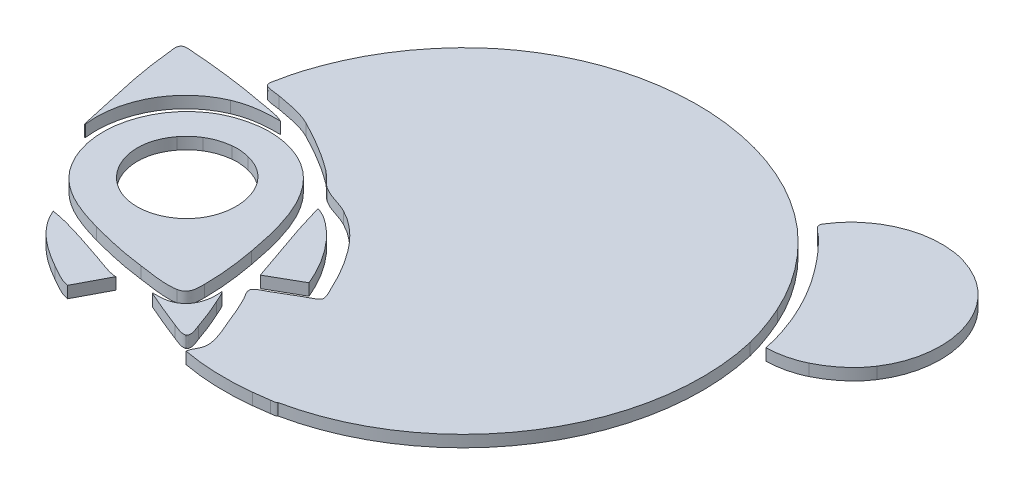
SolidWorks part; units mm, degrees
ref_plane "Alzado" through (0, 0, 0) normal (0, 0, 1) x (1, 0, 0)
ref_plane "Planta" through (0, 0, 0) normal (0, 1, 0) x (1, 0, 0)
ref_plane "Vista lateral" through (0, 0, 0) normal (1, 0, 0) x (0, 0, -1)
sketch "Croquis2" plane through (0, 0, 0) normal (0, 1, 0) x (1, 0, 0)
  line L1 (-10.1434, 10.8277) -> (39.8566, 10.8277)
  line L2 (-10.1434, 10.8277) -> (-10.1434, -4.1723)
  line L3 (-10.1434, -4.1723) -> (39.8566, -4.1723)
  line L4 (39.8566, 10.8277) -> (39.8566, -4.1723)
  line L5 (-10.1434, 10.8277) -> (39.8566, -4.1723) construction
  line L6 (-10.1434, -4.1723) -> (39.8566, 10.8277) construction
  point P0 (14.8566, 3.3277)
  dimension "D1" = 50
  dimension "D2" = 15
sketch "Croquis1" plane through (0, 0, 0) normal (0, 1, 0) x (1, 0, 0)
  line L0 (3.5784, 3.9291) -> (1.8314, 3.9291)
  line L1 (3.9335, 5.4773) -> (5.155, 5.4773)
  line L2 (5.155, 5.4773) -> (5.155, 2.4804)
  line L3 (5.155, 2.4804) -> (5.1692, 2.4804)
  line L4 (3.0387, 4.4262) -> (4.0755, 4.4262)
  line L5 (4.0755, 4.4262) -> (4.0755, -0.829)
  line L6 (4.0755, -0.829) -> (4.0755, -2.0789)
  line L7 (4.2602, -2.5051) -> (4.6579, -2.5051)
  line L8 (4.6579, -2.5051) -> (4.6579, 4.9802)
  line L9 (4.6579, 4.9802) -> (3.9193, 4.9802)
  line L10 (3.9193, 4.9802) -> (3.5926, 4.9716)
  line L11 (3.5926, 4.9716) -> (3.408, 4.8097)
  line L12 (3.408, 4.8097) -> (3.0387, 4.4262)
  line L13 (18.6341, 4.8097) -> (18.6341, 0.7333)
  line L14 (20.0828, -2.3346) -> (20.0828, -1.9369)
  line L15 (19.2164, -0.7154) -> (19.2164, 2.8781)
  line L16 (19.2164, 2.8781) -> (20.0828, 2.8781)
  line L17 (20.0828, 2.8781) -> (20.0828, 3.2758)
  line L18 (20.0828, 3.2758) -> (20.0682, 3.4234)
  line L19 (20.0682, 3.4234) -> (19.8556, 3.4462)
  line L20 (19.8556, 3.4462) -> (19.2164, 3.4462)
  line L21 (19.2164, 3.4462) -> (19.2164, 4.8097)
  line L22 (19.2164, 4.8097) -> (18.6341, 4.8097)
  line L23 (23.8893, 4.8097) -> (23.8893, 0.8044)
  line L24 (25.3239, -2.505) -> (25.3239, -1.9369)
  line L25 (24.4717, -0.7296) -> (24.4717, 2.8781)
  line L26 (24.4717, 2.8781) -> (25.3239, 2.8781)
  line L27 (25.3239, 2.8781) -> (25.3239, 3.4462)
  line L28 (25.3239, 3.4462) -> (24.4717, 3.4462)
  line L29 (24.4717, 3.4462) -> (24.4717, 4.8097)
  line L30 (24.4717, 4.8097) -> (23.8893, 4.8097)
  line L31 (-5.0999, 1.3015) -> (-5.0857, 1.3015)
  line L32 (5.5953, -2.505) -> (6.1634, -2.505)
  line L33 (7.74, -2.505) -> (8.3082, -2.505)
  line L34 (8.3082, -2.505) -> (8.3082, 1.5856)
  line L35 (5.5953, 0.6765) -> (5.5953, -2.505)
  line L36 (12.8249, 0.0267) -> (13.9469, 0.5878)
  line L37 (11.7312, 1.4009) -> (11.7312, -0.3177)
  line L38 (14.2736, -0.7296) -> (13.8759, -0.7296)
  line L39 (17.2989, -2.505) -> (17.725, -2.505)
  line L40 (17.8813, -2.0789) -> (17.8813, -1.0989)
  line L41 (15.1542, 1.2731) -> (15.1542, -0.7864)
  line L42 (15.1542, -0.7864) -> (15.1542, -2.0647)
  line L43 (15.7365, -2.2494) -> (15.7365, -1.525)
  line L44 (15.7365, -1.525) -> (15.7365, 1.1026)
  line L45 (17.2989, 1.1737) -> (17.2989, -0.3035)
  line L46 (17.2989, -0.3035) -> (17.2989, -2.505)
  line L47 (20.4521, 1.2447) -> (20.4521, -0.3319)
  line L48 (28.4202, -0.7296) -> (27.8521, -0.7296)
  line L49 (26.7868, 0.0197) -> (27.8379, 0.5452)
  line L50 (28.4202, 0.989) -> (28.4202, 1.4577)
  line L51 (25.7074, 1.3015) -> (25.7074, -0.6444)
  line L52 (31.687, -0.7864) -> (31.1189, -0.7864)
  line L53 (29.6559, -0.687) -> (29.6559, 1.3583)
  line L54 (31.1189, 1.7276) -> (31.687, 1.7276)
  line L55 (29.0878, 1.6992) -> (29.0878, -0.5876)
  line L56 (34.4851, -2.2352) -> (34.4851, -2.505)
  line L57 (34.4851, -2.505) -> (35.0248, -2.505)
  line L58 (35.0248, -2.505) -> (35.0248, 0.0658)
  line L59 (35.0248, 0.0658) -> (35.0248, 1.8696)
  line L60 (32.312, 1.5288) -> (32.312, -0.4029)
  line L61 (8.6632, 3.4462) -> (8.7709, 2.8213)
  line L62 (8.7709, 2.8213) -> (9.0496, 1.3583)
  line L63 (9.0496, 1.3583) -> (9.7853, -2.505)
  line L64 (10.5409, -1.1415) -> (11.1318, 1.9122)
  line L65 (11.4187, 3.4462) -> (10.8506, 3.4462)
  line L66 (10.041, -0.9853) -> (10.0268, -0.9853)
  line L67 (10.0268, -0.9853) -> (9.2456, 3.4462)
  line L68 (9.2456, 3.4462) -> (8.6632, 3.4462)
  line L69 (-0.2279, 2.4094) -> (-0.0054, 1.685)
  line L70 (-0.0054, 1.685) -> (0.5106, 0.1936)
  line L71 (0.5106, 0.1936) -> (1.306, 0.6481)
  line L72 (-0.4694, -1.5818) -> (-0.4694, -1.596)
  line L73 (-1.7335, -2.5051) -> (-1.3074, -1.6955)
  spline S0 degree 3 poles (8.6064, 5.0654) (8.9077, 5.0656) (9.231, 5.1421) (9.5012, 5.275) knots 0 0 0 0 1 1 1 1
  spline S1 degree 3 poles (9.5012, 5.275) (9.8765, 5.4595) (10.2057, 5.7212) (10.4375, 6.0738) knots 0 0 0 0 1 1 1 1
  spline S2 degree 3 poles (10.4375, 6.0738) (11.1456, 7.1512) (10.8182, 8.6685) (9.6859, 9.3162) knots 0 0 0 0 1 1 1 1
  spline S3 degree 3 poles (9.6859, 9.3162) (9.4504, 9.4509) (9.1882, 9.5508) (8.9189, 9.5924) knots 0 0 0 0 1 1 1 1
  spline S4 degree 3 poles (8.9189, 9.5924) (8.2132, 9.7014) (7.5188, 9.4932) (6.9872, 9.0163) knots 0 0 0 0 1 1 1 1
  spline S5 degree 3 poles (6.9872, 9.0163) (6.8569, 8.8994) (6.7378, 8.7633) (6.642, 8.6163) knots 0 0 0 0 1 1 1 1
  spline S6 degree 3 poles (6.642, 8.6163) (6.6153, 8.5752) (6.5511, 8.5009) (6.5671, 8.4482) knots 0 0 0 0 1 1 1 1
  spline S7 degree 3 poles (6.5671, 8.4482) (6.5982, 8.3461) (6.7844, 8.2366) (6.8594, 8.1618) knots 0 0 0 0 1 1 1 1
  spline S8 degree 3 poles (6.8594, 8.1618) (7.0821, 7.9394) (7.2857, 7.7003) (7.4783, 7.4516) knots 0 0 0 0 1 1 1 1
  spline S9 degree 3 poles (7.4783, 7.4516) (8.0092, 6.7663) (8.4305, 5.9176) (8.6064, 5.0654) knots 0 0 0 0 1 1 1 1
  spline S10 degree 3 poles (1.249, -2.4482) (1.8259, -2.5553) (2.4283, -2.5697) (3.0103, -2.5074) knots 0 0 0 0 1 1 1 1
  spline S11 degree 3 poles (3.0103, -2.5074) (3.1485, -2.4926) (3.2849, -2.4771) (3.4222, -2.4541) knots 0 0 0 0 1 1 1 1
  spline S12 degree 3 poles (3.4222, -2.4541) (3.4634, -2.4472) (3.536, -2.4479) (3.5638, -2.4115) knots 0 0 0 0 1 1 1 1
  spline S13 degree 3 poles (3.5638, -2.4115) (3.6258, -2.3302) (3.5784, -2.0665) (3.5784, -1.9653) knots 0 0 0 0 1 1 1 1
  spline S14 degree 3 poles (3.5784, -1.9653) (3.5784, -1.5582) (3.5826, -1.1506) (3.5785, -0.7438) knots 0 0 0 0 1 1 1 1
  spline S15 degree 3 poles (3.5785, -0.7438) (3.5624, 0.8135) (3.5784, 2.3718) (3.5784, 3.9291) knots 0 0 0 0 1 1 1 1
  spline S16 degree 3 poles (1.8314, 3.9291) (2.196, 4.2937) (2.5619, 4.657) (2.9251, 5.0228) knots 0 0 0 0 1 1 1 1
  spline S17 degree 3 poles (2.9251, 5.0228) (3.0505, 5.1491) (3.2259, 5.4068) (3.3938, 5.4687) knots 0 0 0 0 1 1 1 1
  spline S18 degree 3 poles (3.3938, 5.4687) (3.5397, 5.5225) (3.7781, 5.4773) (3.9335, 5.4773) knots 0 0 0 0 1 1 1 1
  spline S19 degree 3 poles (5.1692, 2.4804) (5.1849, 2.6775) (5.2637, 2.8864) (5.3504, 3.0627) knots 0 0 0 0 1 1 1 1
  spline S20 degree 3 poles (5.3504, 3.0627) (5.4291, 3.2228) (5.5273, 3.3749) (5.6523, 3.503) knots 0 0 0 0 1 1 1 1
  spline S21 degree 3 poles (5.6523, 3.503) (6.1635, 4.0269) (6.9766, 4.092) (7.669, 4.0261) knots 0 0 0 0 1 1 1 1
  spline S22 degree 3 poles (7.669, 4.0261) (7.9276, 4.0015) (8.1757, 3.9433) (8.436, 3.9433) knots 0 0 0 0 1 1 1 1
  spline S23 degree 3 poles (8.436, 3.9433) (8.4211, 4.6648) (8.1948, 5.4069) (7.9006, 6.0596) knots 0 0 0 0 1 1 1 1
  spline S24 degree 3 poles (7.9006, 6.0596) (7.6039, 6.7178) (7.1847, 7.3109) (6.6748, 7.8209) knots 0 0 0 0 1 1 1 1
  spline S25 degree 3 poles (6.6748, 7.8209) (4.3405, 10.1551) (0.3296, 10.1882) (-1.9888, 7.7924) knots 0 0 0 0 1 1 1 1
  spline S26 degree 3 poles (-1.9888, 7.7924) (-2.5824, 7.179) (-3.048, 6.4468) (-3.3469, 5.6477) knots 0 0 0 0 1 1 1 1
  spline S27 degree 3 poles (-3.3469, 5.6477) (-3.4496, 5.373) (-3.5439, 5.0853) (-3.5932, 4.7955) knots 0 0 0 0 1 1 1 1
  spline S28 degree 3 poles (-3.5932, 4.7955) (-3.6044, 4.7295) (-3.6663, 4.5655) (-3.6223, 4.5076) knots 0 0 0 0 1 1 1 1
  spline S29 degree 3 poles (-3.6223, 4.5076) (-3.5662, 4.4338) (-3.3265, 4.4339) (-3.2393, 4.4176) knots 0 0 0 0 1 1 1 1
  spline S30 degree 3 poles (-3.2393, 4.4176) (-2.9214, 4.358) (-2.5794, 4.305) (-2.2876, 4.1591) knots 0 0 0 0 1 1 1 1
  spline S31 degree 3 poles (-2.2876, 4.1591) (-1.8381, 3.9343) (-1.3834, 3.6639) (-0.9809, 3.3625) knots 0 0 0 0 1 1 1 1
  spline S32 degree 3 poles (-0.9809, 3.3625) (-0.8218, 3.2433) (-0.7083, 3.076) (-0.5406, 2.9695) knots 0 0 0 0 1 1 1 1
  spline S33 degree 3 poles (-0.5406, 2.9695) (-0.3336, 2.8379) (-0.0782, 2.7996) (0.1412, 2.6899) knots 0 0 0 0 1 1 1 1
  spline S34 degree 3 poles (0.1412, 2.6899) (0.5113, 2.5048) (0.836, 2.1978) (1.0843, 1.8696) knots 0 0 0 0 1 1 1 1
  spline S35 degree 3 poles (1.0843, 1.8696) (1.33, 1.5449) (1.5407, 1.1895) (1.7079, 0.8186) knots 0 0 0 0 1 1 1 1
  spline S36 degree 3 poles (1.7079, 0.8186) (1.7431, 0.7404) (1.8858, 0.5189) (1.8243, 0.4405) knots 0 0 0 0 1 1 1 1
  spline S37 degree 3 poles (1.8243, 0.4405) (1.7648, 0.3647) (1.63, 0.3142) (1.5473, 0.2668) knots 0 0 0 0 1 1 1 1
  spline S38 degree 3 poles (1.5473, 0.2668) (1.3568, 0.1574) (1.1682, 0.0444) (0.9792, -0.0677) knots 0 0 0 0 1 1 1 1
  spline S39 degree 3 poles (0.9792, -0.0677) (0.9056, -0.1113) (0.7125, -0.1778) (0.7026, -0.2753) knots 0 0 0 0 1 1 1 1
  spline S40 degree 3 poles (0.7026, -0.2753) (0.6938, -0.3635) (0.7928, -0.4849) (0.8328, -0.5592) knots 0 0 0 0 1 1 1 1
  spline S41 degree 3 poles (0.8328, -0.5592) (0.9419, -0.7624) (1.0292, -0.9842) (1.1148, -1.1983) knots 0 0 0 0 1 1 1 1
  spline S42 degree 3 poles (1.1148, -1.1983) (1.2129, -1.4436) (1.3946, -1.782) (1.3874, -2.0505) knots 0 0 0 0 1 1 1 1
  spline S43 degree 3 poles (1.3874, -2.0505) (1.3833, -2.2048) (1.2596, -2.3074) (1.249, -2.4482) knots 0 0 0 0 1 1 1 1
  spline S44 degree 3 poles (4.0755, -2.0789) (4.0755, -2.1593) (4.0324, -2.4382) (4.0983, -2.4904) knots 0 0 0 0 1 1 1 1
  spline S45 degree 3 poles (4.0983, -2.4904) (4.1355, -2.5199) (4.2158, -2.5051) (4.2602, -2.5051) knots 0 0 0 0 1 1 1 1
  spline S46 degree 3 poles (18.6341, 0.7333) (18.6341, 0.0083) (18.5456, -0.7838) (18.6909, -1.4966) knots 0 0 0 0 1 1 1 1
  spline S47 degree 3 poles (18.6909, -1.4966) (18.793, -1.9969) (19.1188, -2.3957) (19.6425, -2.4747) knots 0 0 0 0 1 1 1 1
  spline S48 degree 3 poles (19.6425, -2.4747) (19.7238, -2.487) (20.0105, -2.5551) (20.0682, -2.4823) knots 0 0 0 0 1 1 1 1
  spline S49 degree 3 poles (20.0682, -2.4823) (20.0957, -2.4475) (20.0828, -2.3759) (20.0828, -2.3346) knots 0 0 0 0 1 1 1 1
  spline S50 degree 3 poles (20.0828, -1.9369) (19.9348, -1.9369) (19.7843, -1.944) (19.6425, -1.893) knots 0 0 0 0 1 1 1 1
  spline S51 degree 3 poles (19.6425, -1.893) (19.1744, -1.7245) (19.2164, -1.1155) (19.2164, -0.7154) knots 0 0 0 0 1 1 1 1
  spline S52 degree 3 poles (23.8893, 0.8044) (23.8893, 0.0865) (23.8209, -0.6716) (23.9219, -1.383) knots 0 0 0 0 1 1 1 1
  spline S53 degree 3 poles (23.9219, -1.383) (23.9774, -1.7751) (24.1589, -2.173) (24.5285, -2.3577) knots 0 0 0 0 1 1 1 1
  spline S54 degree 3 poles (24.5285, -2.3577) (24.7735, -2.4803) (25.0542, -2.505) (25.3239, -2.505) knots 0 0 0 0 1 1 1 1
  spline S55 degree 3 poles (25.3239, -1.9369) (25.1804, -1.9369) (25.0351, -1.9424) (24.8978, -1.893) knots 0 0 0 0 1 1 1 1
  spline S56 degree 3 poles (24.8978, -1.893) (24.4304, -1.7248) (24.4717, -1.1296) (24.4717, -0.7296) knots 0 0 0 0 1 1 1 1
  spline S57 degree 3 poles (-5.0857, 1.3015) (-5.2118, 2.2995) (-4.6942, 3.2922) (-3.7506, 3.6958) knots 0 0 0 0 1 1 1 1
  spline S58 degree 3 poles (-3.7506, 3.6958) (-3.393, 3.8487) (-3.0397, 3.8723) (-2.6569, 3.8723) knots 0 0 0 0 1 1 1 1
  spline S59 degree 3 poles (-2.6569, 3.8723) (-2.8408, 3.9708) (-3.1066, 3.9878) (-3.3103, 4.0285) knots 0 0 0 0 1 1 1 1
  spline S60 degree 3 poles (-3.3103, 4.0285) (-3.8355, 4.1336) (-4.3684, 4.2018) (-4.9011, 4.2534) knots 0 0 0 0 1 1 1 1
  spline S61 degree 3 poles (-4.9011, 4.2534) (-5.0712, 4.2699) (-5.2428, 4.2744) (-5.4124, 4.2944) knots 0 0 0 0 1 1 1 1
  spline S62 degree 3 poles (-5.4124, 4.2944) (-5.4785, 4.3021) (-5.5696, 4.3043) (-5.6087, 4.2386) knots 0 0 0 0 1 1 1 1
  spline S63 degree 3 poles (-5.6087, 4.2386) (-5.6475, 4.1732) (-5.6211, 4.0706) (-5.6136, 4.0001) knots 0 0 0 0 1 1 1 1
  spline S64 degree 3 poles (-5.6136, 4.0001) (-5.5938, 3.8152) (-5.5734, 3.6303) (-5.5462, 3.4462) knots 0 0 0 0 1 1 1 1
  spline S65 degree 3 poles (-5.5462, 3.4462) (-5.4383, 2.7175) (-5.2486, 2.0198) (-5.0999, 1.3015) knots 0 0 0 0 1 1 1 1
  spline S66 degree 3 poles (6.1634, -2.505) (6.1634, -1.0898) (6.1467, 0.3266) (6.1635, 1.7418) knots 0 0 0 0 1 1 1 1
  spline S67 degree 3 poles (6.1635, 1.7418) (6.169, 2.2046) (6.2911, 2.9193) (6.8736, 2.962) knots 0 0 0 0 1 1 1 1
  spline S68 degree 3 poles (6.8736, 2.962) (7.5002, 3.0079) (7.7269, 2.3808) (7.7398, 1.8554) knots 0 0 0 0 1 1 1 1
  spline S69 degree 3 poles (7.7398, 1.8554) (7.7754, 0.4039) (7.74, -1.053) (7.74, -2.505) knots 0 0 0 0 1 1 1 1
  spline S70 degree 3 poles (8.3082, 1.5856) (8.3082, 2.1988) (8.2853, 2.9291) (7.7258, 3.3178) knots 0 0 0 0 1 1 1 1
  spline S71 degree 3 poles (7.7258, 3.3178) (6.9874, 3.8309) (5.9192, 3.4358) (5.6931, 2.5798) knots 0 0 0 0 1 1 1 1
  spline S72 degree 3 poles (5.6931, 2.5798) (5.5313, 1.9677) (5.5953, 1.3043) (5.5953, 0.6765) knots 0 0 0 0 1 1 1 1
  spline S73 degree 3 poles (13.8759, -0.7296) (13.8759, -1.0655) (13.8736, -1.4161) (13.6835, -1.7096) knots 0 0 0 0 1 1 1 1
  spline S74 degree 3 poles (13.6835, -1.7096) (13.4417, -2.0828) (12.9078, -2.1527) (12.5989, -1.8232) knots 0 0 0 0 1 1 1 1
  spline S75 degree 3 poles (12.5989, -1.8232) (12.4436, -1.6576) (12.3743, -1.4322) (12.3384, -1.2125) knots 0 0 0 0 1 1 1 1
  spline S76 degree 3 poles (12.3384, -1.2125) (12.3002, -0.9785) (12.3135, -0.7388) (12.3135, -0.5024) knots 0 0 0 0 1 1 1 1
  spline S77 degree 3 poles (12.3135, -0.5024) (12.3135, -0.431) (12.2885, -0.3001) (12.3282, -0.238) knots 0 0 0 0 1 1 1 1
  spline S78 degree 3 poles (12.3282, -0.238) (12.4037, -0.1195) (12.6997, -0.0359) (12.8249, 0.0267) knots 0 0 0 0 1 1 1 1
  spline S79 degree 3 poles (13.9469, 0.5878) (14.0847, 0.6567) (14.3335, 0.7261) (14.4355, 0.8418) knots 0 0 0 0 1 1 1 1
  spline S80 degree 3 poles (14.4355, 0.8418) (14.5115, 0.928) (14.4583, 1.2316) (14.4583, 1.3441) knots 0 0 0 0 1 1 1 1
  spline S81 degree 3 poles (14.4583, 1.3441) (14.4583, 1.8539) (14.4759, 2.3949) (14.2414, 2.8639) knots 0 0 0 0 1 1 1 1
  spline S82 degree 3 poles (14.2414, 2.8639) (13.8167, 3.7132) (12.4813, 3.7693) (11.9932, 2.9491) knots 0 0 0 0 1 1 1 1
  spline S83 degree 3 poles (11.9932, 2.9491) (11.7168, 2.4845) (11.7312, 1.922) (11.7312, 1.4009) knots 0 0 0 0 1 1 1 1
  spline S84 degree 3 poles (11.7312, -0.3177) (11.7312, -0.7614) (11.7137, -1.2075) (11.8367, -1.6386) knots 0 0 0 0 1 1 1 1
  spline S85 degree 3 poles (11.8367, -1.6386) (12.0444, -2.3666) (12.7389, -2.7261) (13.464, -2.5491) knots 0 0 0 0 1 1 1 1
  spline S86 degree 3 poles (13.464, -2.5491) (14.0706, -2.401) (14.363, -1.8326) (14.4321, -1.2551) knots 0 0 0 0 1 1 1 1
  spline S87 degree 3 poles (14.4321, -1.2551) (14.4472, -1.1283) (14.4583, -0.9994) (14.4583, -0.8716) knots 0 0 0 0 1 1 1 1
  spline S88 degree 3 poles (14.4583, -0.8716) (14.4583, -0.8345) (14.4689, -0.7707) (14.4355, -0.7442) knots 0 0 0 0 1 1 1 1
  spline S89 degree 3 poles (14.4355, -0.7442) (14.3983, -0.7148) (14.3179, -0.7296) (14.2736, -0.7296) knots 0 0 0 0 1 1 1 1
  spline S90 degree 3 poles (17.725, -2.505) (17.7682, -2.505) (17.8493, -2.5197) (17.8728, -2.4721) knots 0 0 0 0 1 1 1 1
  spline S91 degree 3 poles (17.8728, -2.4721) (17.9191, -2.3779) (17.8813, -2.1835) (17.8813, -2.0789) knots 0 0 0 0 1 1 1 1
  spline S92 degree 3 poles (17.8813, -1.0989) (17.8813, -0.0732) (17.9125, 0.9594) (17.8676, 1.9833) knots 0 0 0 0 1 1 1 1
  spline S93 degree 3 poles (17.8676, 1.9833) (17.846, 2.4772) (17.7168, 3.0451) (17.2705, 3.3313) knots 0 0 0 0 1 1 1 1
  spline S94 degree 3 poles (17.2705, 3.3313) (16.5801, 3.7741) (15.5934, 3.4929) (15.3023, 2.7218) knots 0 0 0 0 1 1 1 1
  spline S95 degree 3 poles (15.3023, 2.7218) (15.1284, 2.2611) (15.1542, 1.7567) (15.1542, 1.2731) knots 0 0 0 0 1 1 1 1
  spline S96 degree 3 poles (15.1542, -2.0647) (15.1542, -2.1471) (15.1097, -2.4372) (15.1769, -2.4904) knots 0 0 0 0 1 1 1 1
  spline S97 degree 3 poles (15.1769, -2.4904) (15.2274, -2.5303) (15.3627, -2.505) (15.4241, -2.505) knots 0 0 0 0 1 1 1 1
  spline S98 degree 3 poles (15.4241, -2.505) (15.4937, -2.505) (15.6573, -2.5352) (15.7138, -2.4904) knots 0 0 0 0 1 1 1 1
  spline S99 degree 3 poles (15.7138, -2.4904) (15.7625, -2.4518) (15.7365, -2.3053) (15.7365, -2.2494) knots 0 0 0 0 1 1 1 1
  spline S100 degree 3 poles (15.7365, 1.1026) (15.7365, 1.5661) (15.6716, 2.0888) (15.8688, 2.523) knots 0 0 0 0 1 1 1 1
  spline S101 degree 3 poles (15.8688, 2.523) (16.1063, 3.0459) (16.8034, 3.1218) (17.1133, 2.6224) knots 0 0 0 0 1 1 1 1
  spline S102 degree 3 poles (17.1133, 2.6224) (17.3724, 2.2051) (17.2989, 1.6412) (17.2989, 1.1737) knots 0 0 0 0 1 1 1 1
  spline S103 degree 3 poles (21.6736, 3.5254) (21.1756, 3.4592) (20.7933, 3.2202) (20.6056, 2.736) knots 0 0 0 0 1 1 1 1
  spline S104 degree 3 poles (20.6056, 2.736) (20.4224, 2.2629) (20.4521, 1.7424) (20.4521, 1.2447) knots 0 0 0 0 1 1 1 1
  spline S105 degree 3 poles (20.4521, -0.3319) (20.4521, -0.7523) (20.4386, -1.1711) (20.5426, -1.5818) knots 0 0 0 0 1 1 1 1
  spline S106 degree 3 poles (20.5426, -1.5818) (20.7266, -2.3081) (21.3444, -2.6751) (22.0713, -2.572) knots 0 0 0 0 1 1 1 1
  spline S107 degree 3 poles (22.0713, -2.572) (22.632, -2.4925) (22.9742, -2.0485) (23.1029, -1.525) knots 0 0 0 0 1 1 1 1
  spline S108 degree 3 poles (23.1029, -1.525) (23.2759, -0.8203) (23.1792, -0.0161) (23.1792, 0.705) knots 0 0 0 0 1 1 1 1
  spline S109 degree 3 poles (23.1792, 0.705) (23.1792, 1.3385) (23.2571, 2.0402) (23.056, 2.6508) knots 0 0 0 0 1 1 1 1
  spline S110 degree 3 poles (23.056, 2.6508) (22.8601, 3.2453) (22.3012, 3.6088) (21.6736, 3.5254) knots 0 0 0 0 1 1 1 1
  spline S111 degree 3 poles (27.8521, -0.7296) (27.8521, -1.0649) (27.8467, -1.4176) (27.6575, -1.7096) knots 0 0 0 0 1 1 1 1
  spline S112 degree 3 poles (27.6575, -1.7096) (27.395, -2.115) (26.8232, -2.1464) (26.5244, -1.7665) knots 0 0 0 0 1 1 1 1
  spline S113 degree 3 poles (26.5244, -1.7665) (26.2184, -1.3775) (26.2866, -0.7937) (26.2897, -0.3319) knots 0 0 0 0 1 1 1 1
  spline S114 degree 3 poles (26.2897, -0.3319) (26.291, -0.1431) (26.6374, -0.055) (26.7868, 0.0197) knots 0 0 0 0 1 1 1 1
  spline S115 degree 3 poles (27.8379, 0.5452) (28.0134, 0.633) (28.2117, 0.7076) (28.3755, 0.8157) knots 0 0 0 0 1 1 1 1
  spline S116 degree 3 poles (28.3755, 0.8157) (28.4344, 0.8546) (28.4202, 0.9268) (28.4202, 0.989) knots 0 0 0 0 1 1 1 1
  spline S117 degree 3 poles (28.4202, 1.4577) (28.4202, 2.1038) (28.4332, 2.8943) (27.8379, 3.3121) knots 0 0 0 0 1 1 1 1
  spline S118 degree 3 poles (27.8379, 3.3121) (27.4055, 3.6156) (26.7003, 3.6153) (26.2755, 3.2969) knots 0 0 0 0 1 1 1 1
  spline S119 degree 3 poles (26.2755, 3.2969) (26.0635, 3.1379) (25.9265, 2.9118) (25.8383, 2.665) knots 0 0 0 0 1 1 1 1
  spline S120 degree 3 poles (25.8383, 2.665) (25.6821, 2.2279) (25.7074, 1.7578) (25.7074, 1.3015) knots 0 0 0 0 1 1 1 1
  spline S121 degree 3 poles (25.7074, -0.6444) (25.7074, -1.134) (25.7268, -1.6575) (26.0108, -2.0789) knots 0 0 0 0 1 1 1 1
  spline S122 degree 3 poles (26.0108, -2.0789) (26.4425, -2.7199) (27.5261, -2.7746) (28.0326, -2.1926) knots 0 0 0 0 1 1 1 1
  spline S123 degree 3 poles (28.0326, -2.1926) (28.3857, -1.7868) (28.4307, -1.2407) (28.4202, -0.7296) knots 0 0 0 0 1 1 1 1
  spline S124 degree 3 poles (31.1189, -0.7864) (31.1189, -1.0988) (31.1247, -1.4528) (30.9433, -1.7238) knots 0 0 0 0 1 1 1 1
  spline S125 degree 3 poles (30.9433, -1.7238) (30.6722, -2.129) (30.0842, -2.1175) (29.8221, -1.7096) knots 0 0 0 0 1 1 1 1
  spline S126 degree 3 poles (29.8221, -1.7096) (29.6349, -1.4183) (29.6559, -1.0185) (29.6559, -0.687) knots 0 0 0 0 1 1 1 1
  spline S127 degree 3 poles (29.6559, 1.3583) (29.6559, 1.7297) (29.6099, 2.157) (29.7534, 2.5088) knots 0 0 0 0 1 1 1 1
  spline S128 degree 3 poles (29.7534, 2.5088) (29.9487, 2.9872) (30.5759, 3.1426) (30.9125, 2.7076) knots 0 0 0 0 1 1 1 1
  spline S129 degree 3 poles (30.9125, 2.7076) (31.1239, 2.4346) (31.1189, 2.0549) (31.1189, 1.7276) knots 0 0 0 0 1 1 1 1
  spline S130 degree 3 poles (31.687, 1.7276) (31.687, 2.2245) (31.6629, 2.7337) (31.3257, 3.1337) knots 0 0 0 0 1 1 1 1
  spline S131 degree 3 poles (31.3257, 3.1337) (30.8391, 3.7111) (29.7916, 3.6561) (29.3683, 3.0343) knots 0 0 0 0 1 1 1 1
  spline S132 degree 3 poles (29.3683, 3.0343) (29.0996, 2.6396) (29.0878, 2.1582) (29.0878, 1.6992) knots 0 0 0 0 1 1 1 1
  spline S133 degree 3 poles (29.0878, -0.5876) (29.0878, -1.0915) (29.0672, -1.6212) (29.3497, -2.0647) knots 0 0 0 0 1 1 1 1
  spline S134 degree 3 poles (29.3497, -2.0647) (29.7671, -2.7203) (30.8463, -2.7798) (31.3396, -2.1784) knots 0 0 0 0 1 1 1 1
  spline S135 degree 3 poles (31.3396, -2.1784) (31.6657, -1.7805) (31.687, -1.2751) (31.687, -0.7864) knots 0 0 0 0 1 1 1 1
  spline S136 degree 3 poles (35.0248, 1.8696) (35.0248, 2.3295) (34.9257, 2.8674) (34.5821, 3.2007) knots 0 0 0 0 1 1 1 1
  spline S137 degree 3 poles (34.5821, 3.2007) (34.04, 3.7265) (32.9734, 3.6293) (32.5763, 2.9775) knots 0 0 0 0 1 1 1 1
  spline S138 degree 3 poles (32.5763, 2.9775) (32.3087, 2.5382) (32.312, 2.025) (32.312, 1.5288) knots 0 0 0 0 1 1 1 1
  spline S139 degree 3 poles (32.312, -0.4029) (32.312, -0.8505) (32.2849, -1.3096) (32.4405, -1.738) knots 0 0 0 0 1 1 1 1
  spline S140 degree 3 poles (32.4405, -1.738) (32.5287, -1.9806) (32.67, -2.209) (32.8801, -2.3641) knots 0 0 0 0 1 1 1 1
  spline S141 degree 3 poles (32.8801, -2.3641) (33.3618, -2.7195) (34.0705, -2.6495) (34.4851, -2.2352) knots 0 0 0 0 1 1 1 1
  spline S142 degree 3 poles (-2.7989, 3.4828) (-3.1486, 3.4363) (-3.4873, 3.3276) (-3.779, 3.1235) knots 0 0 0 0 1 1 1 1
  spline S143 degree 3 poles (-3.779, 3.1235) (-4.7667, 2.4324) (-4.984, 1.0203) (-4.2493, 0.0658) knots 0 0 0 0 1 1 1 1
  spline S144 degree 3 poles (-4.2493, 0.0658) (-3.8559, -0.4453) (-3.2576, -0.6681) (-2.6569, -0.8351) knots 0 0 0 0 1 1 1 1
  spline S145 degree 3 poles (-2.6569, -0.8351) (-2.186, -0.966) (-1.7081, -1.0714) (-1.2224, -1.1295) knots 0 0 0 0 1 1 1 1
  spline S146 degree 3 poles (-1.2224, -1.1295) (-0.9209, -1.1656) (-0.5431, -1.2464) (-0.2423, -1.1936) knots 0 0 0 0 1 1 1 1
  spline S147 degree 3 poles (-0.2423, -1.1936) (0.0019, -1.1508) (-0.0009, -0.9264) (-0.0009, -0.7296) knots 0 0 0 0 1 1 1 1
  spline S148 degree 3 poles (-0.0009, -0.7296) (-0.0009, -0.2796) (-0.0544, 0.1771) (-0.1374, 0.6197) knots 0 0 0 0 1 1 1 1
  spline S149 degree 3 poles (-0.1374, 0.6197) (-0.3277, 1.6352) (-0.6234, 2.7969) (-1.6343, 3.2863) knots 0 0 0 0 1 1 1 1
  spline S150 degree 3 poles (-1.6343, 3.2863) (-1.8009, 3.367) (-1.9786, 3.4216) (-2.1598, 3.4576) knots 0 0 0 0 1 1 1 1
  spline S151 degree 3 poles (-2.1598, 3.4576) (-2.3616, 3.4976) (-2.5944, 3.51) (-2.7989, 3.4828) knots 0 0 0 0 1 1 1 1
  spline S152 degree 3 poles (9.7853, -2.505) (9.8924, -2.505) (10.1743, -2.5557) (10.2599, -2.4904) knots 0 0 0 0 1 1 1 1
  spline S153 degree 3 poles (10.2599, -2.4904) (10.3266, -2.4396) (10.3317, -2.2158) (10.3478, -2.1357) knots 0 0 0 0 1 1 1 1
  spline S154 degree 3 poles (10.3478, -2.1357) (10.4138, -1.8047) (10.477, -1.473) (10.5409, -1.1415) knots 0 0 0 0 1 1 1 1
  spline S155 degree 3 poles (11.1318, 1.9122) (11.194, 2.2342) (11.2559, 2.5563) (11.3193, 2.8781) knots 0 0 0 0 1 1 1 1
  spline S156 degree 3 poles (11.3193, 2.8781) (11.3558, 3.0635) (11.4147, 3.2567) (11.4187, 3.4462) knots 0 0 0 0 1 1 1 1
  spline S157 degree 3 poles (10.8506, 3.4462) (10.658, 2.4534) (10.4702, 1.4588) (10.2907, 0.4635) knots 0 0 0 0 1 1 1 1
  spline S158 degree 3 poles (10.2907, 0.4635) (10.2062, -0.0049) (10.0423, -0.5084) (10.041, -0.9853) knots 0 0 0 0 1 1 1 1
  spline S159 degree 3 poles (12.3135, 0.4351) (12.3135, 0.9401) (12.2919, 1.4504) (12.3142, 1.9548) knots 0 0 0 0 1 1 1 1
  spline S160 degree 3 poles (12.3142, 1.9548) (12.3217, 2.1278) (12.3608, 2.3033) (12.4179, 2.4662) knots 0 0 0 0 1 1 1 1
  spline S161 degree 3 poles (12.4179, 2.4662) (12.5939, 2.9676) (13.2485, 3.1556) (13.6178, 2.736) knots 0 0 0 0 1 1 1 1
  spline S162 degree 3 poles (13.6178, 2.736) (13.8624, 2.4581) (13.876, 2.0347) (13.876, 1.685) knots 0 0 0 0 1 1 1 1
  spline S163 degree 3 poles (13.876, 1.685) (13.876, 1.5734) (13.9257, 1.3033) (13.8614, 1.2111) knots 0 0 0 0 1 1 1 1
  spline S164 degree 3 poles (13.8614, 1.2111) (13.7922, 1.112) (13.5574, 1.0463) (13.4499, 0.9925) knots 0 0 0 0 1 1 1 1
  spline S165 degree 3 poles (13.4499, 0.9925) (13.0887, 0.8119) (12.7012, 0.5467) (12.3135, 0.4351) knots 0 0 0 0 1 1 1 1
  spline S166 degree 3 poles (21.7021, 2.9592) (22.1935, 3.0232) (22.4782, 2.6546) (22.562, 2.2105) knots 0 0 0 0 1 1 1 1
  spline S167 degree 3 poles (22.562, 2.2105) (22.6598, 1.6913) (22.5969, 1.1183) (22.5969, 0.5913) knots 0 0 0 0 1 1 1 1
  spline S168 degree 3 poles (22.5969, 0.5913) (22.5969, 0.0555) (22.6608, -0.5254) (22.591, -1.0563) knots 0 0 0 0 1 1 1 1
  spline S169 degree 3 poles (22.591, -1.0563) (22.5357, -1.4759) (22.4111, -1.9678) (21.9152, -2.0322) knots 0 0 0 0 1 1 1 1
  spline S170 degree 3 poles (21.9152, -2.0322) (21.4322, -2.095) (21.1509, -1.7154) (21.0695, -1.2835) knots 0 0 0 0 1 1 1 1
  spline S171 degree 3 poles (21.0695, -1.2835) (20.974, -0.7776) (21.0345, -0.2205) (21.0345, 0.293) knots 0 0 0 0 1 1 1 1
  spline S172 degree 3 poles (21.0345, 0.293) (21.0345, 0.8494) (20.9732, 1.4453) (21.0387, 1.9975) knots 0 0 0 0 1 1 1 1
  spline S173 degree 3 poles (21.0387, 1.9975) (21.0868, 2.4044) (21.2242, 2.8969) (21.7021, 2.9592) knots 0 0 0 0 1 1 1 1
  spline S174 degree 3 poles (26.2898, 0.4351) (26.2898, 0.9495) (26.268, 1.4693) (26.2905, 1.9833) knots 0 0 0 0 1 1 1 1
  spline S175 degree 3 poles (26.2905, 1.9833) (26.2977, 2.1479) (26.3339, 2.3277) (26.3957, 2.4804) knots 0 0 0 0 1 1 1 1
  spline S176 degree 3 poles (26.3957, 2.4804) (26.5848, 2.947) (27.2097, 3.1662) (27.5799, 2.7502) knots 0 0 0 0 1 1 1 1
  spline S177 degree 3 poles (27.5799, 2.7502) (27.8277, 2.4716) (27.8523, 2.0525) (27.8523, 1.6992) knots 0 0 0 0 1 1 1 1
  spline S178 degree 3 poles (27.8523, 1.6992) (27.8523, 1.5847) (27.9037, 1.3056) (27.8377, 1.2111) knots 0 0 0 0 1 1 1 1
  spline S179 degree 3 poles (27.8377, 1.2111) (27.7685, 1.112) (27.5337, 1.0463) (27.4262, 0.9925) knots 0 0 0 0 1 1 1 1
  spline S180 degree 3 poles (27.4262, 0.9925) (27.065, 0.8119) (26.6775, 0.5467) (26.2898, 0.4351) knots 0 0 0 0 1 1 1 1
  spline S181 degree 3 poles (33.5479, 2.9592) (34.0622, 3.0262) (34.3477, 2.6316) (34.4222, 2.1679) knots 0 0 0 0 1 1 1 1
  spline S182 degree 3 poles (34.4222, 2.1679) (34.5004, 1.6824) (34.4569, 1.1672) (34.4569, 0.6765) knots 0 0 0 0 1 1 1 1
  spline S183 degree 3 poles (34.4569, 0.6765) (34.4569, 0.0893) (34.496, -0.5144) (34.4403, -1.0989) knots 0 0 0 0 1 1 1 1
  spline S184 degree 3 poles (34.4403, -1.0989) (34.4014, -1.5073) (34.2403, -1.9718) (33.7751, -2.0322) knots 0 0 0 0 1 1 1 1
  spline S185 degree 3 poles (33.7751, -2.0322) (33.2618, -2.0989) (32.9768, -1.687) (32.9106, -1.2267) knots 0 0 0 0 1 1 1 1
  spline S186 degree 3 poles (32.9106, -1.2267) (32.8431, -0.7573) (32.8803, -0.2658) (32.8803, 0.2078) knots 0 0 0 0 1 1 1 1
  spline S187 degree 3 poles (32.8803, 0.2078) (32.8803, 0.8165) (32.853, 1.4333) (32.8958, 2.0401) knots 0 0 0 0 1 1 1 1
  spline S188 degree 3 poles (32.8958, 2.0401) (32.9234, 2.4312) (33.109, 2.902) (33.5479, 2.9592) knots 0 0 0 0 1 1 1 1
  spline S189 degree 3 poles (-2.7277, 2.7036) (-2.5814, 2.7211) (-2.43, 2.7037) (-2.2874, 2.6699) knots 0 0 0 0 1 1 1 1
  spline S190 degree 3 poles (-2.2874, 2.6699) (-1.1935, 2.4111) (-0.9731, 0.8855) (-1.9323, 0.3137) knots 0 0 0 0 1 1 1 1
  spline S191 degree 3 poles (-1.9323, 0.3137) (-2.0844, 0.223) (-2.2536, 0.1625) (-2.4295, 0.1409) knots 0 0 0 0 1 1 1 1
  spline S192 degree 3 poles (-2.4295, 0.1409) (-3.5335, 0.0052) (-4.3235, 1.2936) (-3.6334, 2.1963) knots 0 0 0 0 1 1 1 1
  spline S193 degree 3 poles (-3.6334, 2.1963) (-3.5368, 2.3227) (-3.4182, 2.4341) (-3.2817, 2.5166) knots 0 0 0 0 1 1 1 1
  spline S194 degree 3 poles (-3.2817, 2.5166) (-3.1119, 2.6193) (-2.9245, 2.68) (-2.7277, 2.7036) knots 0 0 0 0 1 1 1 1
  spline S195 degree 3 poles (1.306, 0.6481) (1.0971, 1.15) (0.7734, 1.6633) (0.3686, 2.0283) knots 0 0 0 0 1 1 1 1
  spline S196 degree 3 poles (0.3686, 2.0283) (0.1962, 2.1837) (-0.0003, 2.3438) (-0.2279, 2.4094) knots 0 0 0 0 1 1 1 1
  spline S197 degree 3 poles (0.3828, -0.6586) (0.4278, -1.0147) (0.3325, -1.4031) (-0.0433, -1.5379) knots 0 0 0 0 1 1 1 1
  spline S198 degree 3 poles (-0.0433, -1.5379) (-0.1819, -1.5877) (-0.3247, -1.5818) (-0.4694, -1.5818) knots 0 0 0 0 1 1 1 1
  spline S199 degree 3 poles (-0.4694, -1.596) (-0.137, -1.7344) (0.1856, -1.8843) (0.5248, -2.0072) knots 0 0 0 0 1 1 1 1
  spline S200 degree 3 poles (0.5248, -2.0072) (0.6051, -2.0362) (0.8098, -2.1351) (0.8896, -2.0881) knots 0 0 0 0 1 1 1 1
  spline S201 degree 3 poles (0.8896, -2.0881) (0.9846, -2.0321) (0.8664, -1.797) (0.8421, -1.7239) knots 0 0 0 0 1 1 1 1
  spline S202 degree 3 poles (0.8421, -1.7239) (0.7551, -1.4631) (0.6526, -1.2057) (0.5359, -0.9569) knots 0 0 0 0 1 1 1 1
  spline S203 degree 3 poles (0.5359, -0.9569) (0.4895, -0.8579) (0.453, -0.7434) (0.3828, -0.6586) knots 0 0 0 0 1 1 1 1
  spline S204 degree 3 poles (-3.5657, -1.0421) (-3.3363, -1.5931) (-2.8179, -1.9576) (-2.3158, -2.2412) knots 0 0 0 0 1 1 1 1
  spline S205 degree 3 poles (-2.3158, -2.2412) (-2.1437, -2.3385) (-1.9309, -2.4755) (-1.7335, -2.5051) knots 0 0 0 0 1 1 1 1
  spline S206 degree 3 poles (-1.3074, -1.6955) (-1.5281, -1.6858) (-1.7654, -1.5685) (-1.975, -1.5015) knots 0 0 0 0 1 1 1 1
  spline S207 degree 3 poles (-1.975, -1.5015) (-2.4848, -1.3386) (-3.0358, -1.1201) (-3.5657, -1.0421) knots 0 0 0 0 1 1 1 1
extrude "Saliente-Extruir1" add sketch "Croquis1" along normal blind 0.3
sketch "Croquis3" plane through (0, 0.3, 0) normal (0, 1, 0) x (1, 0, 0)
  line L1 (36.2989, -3.7236) -> (3.9193, -3.7236)
  line L2 (36.2989, -3.7236) -> (36.2989, 4.9802)
  line L3 (36.2989, 4.9802) -> (3.9193, 4.9802)
  line L4 (3.9193, -3.7236) -> (3.9193, 4.9802)
  point P6 (0, 0)
  point P7 (0, 0)
  point P8 (36.2989, -3.7236)
  point P9 (3.9193, 4.9802)
extrude "Cortar-Extruir2" cut sketch "Croquis3" against normal blind 10
sketch "Croquis4" plane through (0, 0.3, 0) normal (0, 1, 0) x (1, 0, 0)
  line L0 (1.249, -2.4482) -> (3.0679, -0.4227)
  line L1 (3.0679, -0.4227) -> (2.3107, 2.1053)
  line L2 (2.3107, 2.1053) -> (0.8822, 3.5928)
  line L3 (0.8822, 3.5928) -> (3.0679, 6.6258)
  line L4 (3.0679, 6.6258) -> (8.2854, 4.9802)
  arc A0 (1.249, -2.4482) -> (8.2854, 4.9802) centre (2.3107, 3.5928) ccw
extrude "Saliente-Extruir2" add sketch "Croquis4" against normal through all
